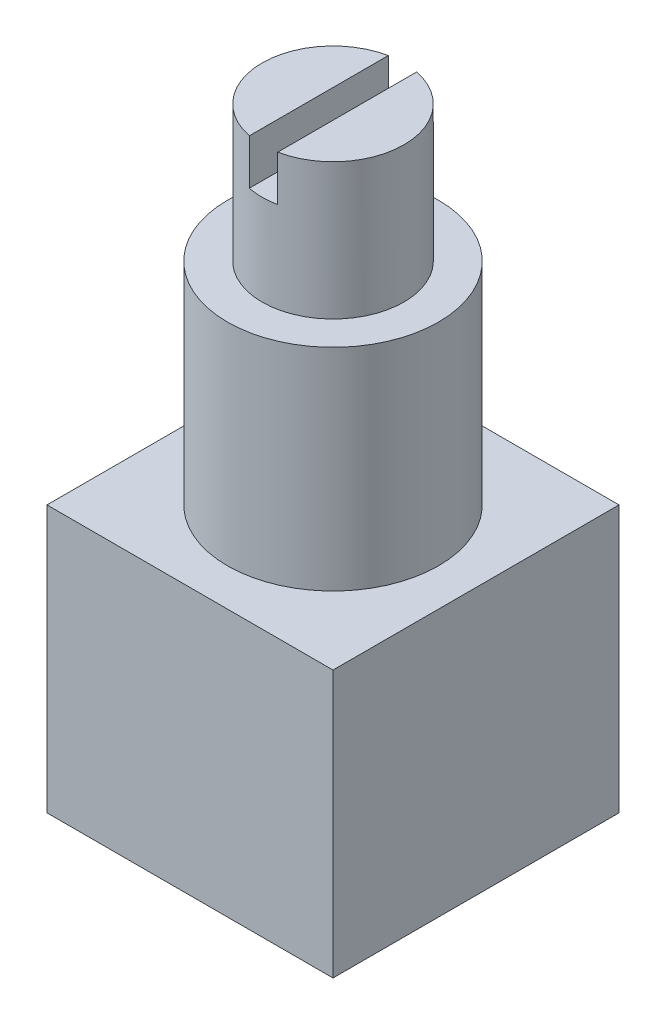
SolidWorks part; units mm, degrees
material "Potentiometer"
ref_plane "Front Plane" through (0, 0, 0) normal (0, 0, 1) x (1, 0, 0)
ref_plane "Top Plane" through (0, 0, 0) normal (0, 1, 0) x (1, 0, 0)
ref_plane "Right Plane" through (0, 0, 0) normal (1, 0, 0) x (0, 0, -1)
sketch "Sketch1" plane through (0, 0, 0) normal (0, 1, 0) x (1, 0, 0)
  line L1 (-6.3, 6.3) -> (6.3, 6.3)
  line L2 (-6.3, 6.3) -> (-6.3, -6.3)
  line L3 (-6.3, -6.3) -> (6.3, -6.3)
  line L4 (6.3, 6.3) -> (6.3, -6.3)
  line L5 (-6.3, 6.3) -> (6.3, -6.3) construction
  line L6 (-6.3, -6.3) -> (6.3, 6.3) construction
  point P0 (0, 0)
  dimension "D1" = 12.6
  dimension "D2" = 12.6
extrude "Boss-Extrude1" add sketch "Sketch1" along normal blind 11.75
sketch "Sketch2" plane through (0, 11.75, 0) normal (0, 1, 0) x (1, 0, 0)
  circle A0 centre (0, 0) radius 4.65
  dimension "D1" = 9.3
extrude "Boss-Extrude2" add sketch "Sketch2" along normal blind 9.3
sketch "Sketch3" plane through (0, 21.05, 0) normal (0, 1, 0) x (1, 0, 0)
  circle A0 centre (0, 0) radius 3.125
  dimension "D1" = 6.25
extrude "Boss-Extrude3" add sketch "Sketch3" along normal blind 6
sketch "Sketch4" plane through (0, 0, 0) normal (0, 0, 1) x (1, 0, 0)
  line L0 (3.125, 27.05) -> (-3.125, 27.05) construction
  line L1 (3.125, 27.05) -> (-3.125, 27.05) construction
  line L2 (0, 27.05) -> (0, 33.9441) construction
  line L4 (0.625, 25.05) -> (-0.625, 25.05)
  line L5 (0.625, 25.05) -> (0.625, 27.05)
  line L6 (0.625, 27.05) -> (-0.625, 27.05)
  line L7 (-0.625, 25.05) -> (-0.625, 27.05)
  line L8 (0.625, 25.05) -> (-0.625, 27.05) construction
  line L9 (0.625, 27.05) -> (-0.625, 25.05) construction
  point P5 (0, 26.05)
  dimension "D1" = 1.25
  dimension "D2" = 2
extrude "Cut-Extrude1" cut sketch "Sketch4" against normal through all and the other way through all
